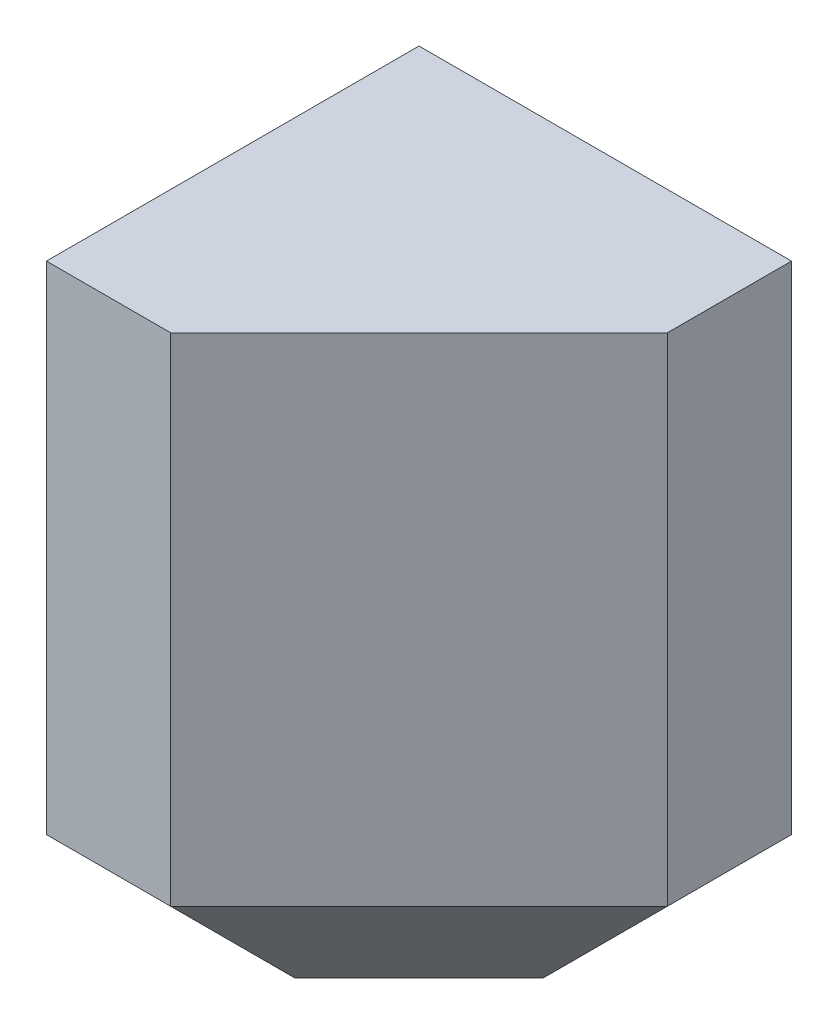
SolidWorks part; units mm, degrees
material "ABS"
ref_plane "Piano frontale" through (0, 0, 0) normal (0, 0, 1) x (1, 0, 0)
ref_plane "Piano superiore" through (0, 0, 0) normal (0, 1, 0) x (1, 0, 0)
ref_plane "Piano destro" through (0, 0, 0) normal (1, 0, 0) x (0, 0, -1)
sketch "Schizzo1" plane through (0, 0, 0) normal (0, 0, 1) x (1, 0, 0)
  line L1 (0, 0) -> (30, 0)
  line L2 (0, 0) -> (0, 40)
  line L3 (0, 40) -> (30, 40)
  line L4 (30, 0) -> (30, 40)
  dimension "D1" = 30
  dimension "D2" = 40
extrude "Estrusione-Estrusione1" add sketch "Schizzo1" along normal blind 30
chamfer "Smusso1" distance 20 angle 45 3 edges at (30, 20, 30) (30, 0, 15) (15, 0, 30)
sketch "Schizzo2" plane through (0, 40, 0) normal (0, 1, 0) x (1, 0, 0)
  line L0 (0, 0) -> (30, 0)
  line L1 (30, 0) -> (30, -10)
  line L2 (30, -10) -> (10, -30)
  line L3 (10, -30) -> (0, -30)
  line L4 (0, -30) -> (0, 0)
extrude "Estrusione-Estrusione2" add sketch "Schizzo2" along normal blind 20
hole_wizard "Foro per Vite M5-1" positions "Schizzo3" profile "Schizzo4" hole size "M5" standard "ISO"
sketch "Schizzo3" plane through (0, 0, 0) normal (-1, 0, 0) x (0, 0, 1)
  line L0 (18, 20) -> (18, 48) construction
  line L2 (0, 60) -> (0, 0) construction
  line L10 (0, 60) -> (30, 60) construction
  point P0 (18, 20)
  point P47 (18, 48)
  dimension "D1" = 18
  dimension "D2" = 12
  dimension "D3" = 28
sketch "Schizzo4" plane through (0, 20, 18) normal (0, 1, 0) x (0, 0, 1)
  line L0 (0, 0) -> (0, 14.6524)
  line L1 (0, 14.6524) -> (2.75, 13)
  line L2 (2.75, 13) -> (2.75, 0)
  line L5 (2.75, 0) -> (0, 0)
  line L10 (0, 14.6524) -> (-2.75, 13) construction
  line L11 (0, -6.35) -> (0, 107.95) construction
  dimension "Hole Dia." = 5.5
  dimension "Hole Depth" = 13
  dimension "Drill Angle" = 118
hole_wizard "Foro per Vite M5-2" positions "Schizzo3D1" profile "Schizzo5" hole size "M5" standard "ISO"
sketch3d "Schizzo3D1"
  line L0 (18, 20, 0) -> (18, 34, 0) construction
  line L2 (0, 60, 0) -> (0, 0, 0) construction
  line L4 (18, 48, 0) -> (18, 34, 0) construction
  line L5 (30, 60, 0) -> (0, 60, 0) construction
  point P2 (18, 20, 0)
  point P21 (18, 48, 0)
  dimension "D1" = 18
  dimension "D2" = 14
  dimension "D3" = 12
  dimension "D4" = 14
sketch "Schizzo5" plane through (18, 20, 0) normal (1, 0, 0) x (0, 1, 0)
  line L0 (0, 0) -> (0, 14.6524)
  line L1 (0, 14.6524) -> (2.75, 13)
  line L2 (2.75, 13) -> (2.75, 0)
  line L5 (2.75, 0) -> (0, 0)
  line L10 (0, 14.6524) -> (-2.75, 13) construction
  line L11 (0, -6.35) -> (0, 107.95) construction
  dimension "Hole Dia." = 5.5
  dimension "Hole Depth" = 13
  dimension "Drill Angle" = 118
sketch "Schizzo6" plane through (0, 0, 0) normal (0, -1, 0) x (1, 0, 0)
  line L0 (30, 10) -> (30, 0) construction
  line L1 (0, 30) -> (30, 30)
  line L2 (0, 30) -> (0, 0)
  line L3 (0, 0) -> (30, 0)
  line L4 (30, 30) -> (30, 0)
extrude "Taglio-Estrusione1" cut sketch "Schizzo6" against normal blind 10
